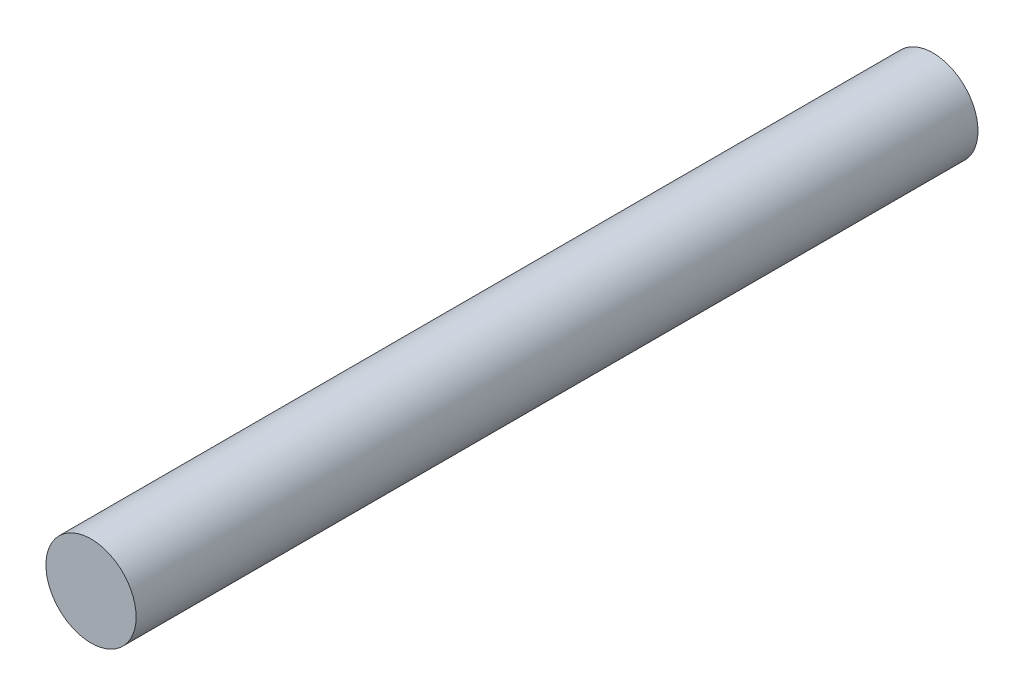
SolidWorks part; units mm, degrees
ref_plane "Front Plane" through (0, 0, 0) normal (0, 0, 1) x (1, 0, 0)
ref_plane "Top Plane" through (0, 0, 0) normal (0, 1, 0) x (1, 0, 0)
ref_plane "Right Plane" through (0, 0, 0) normal (1, 0, 0) x (0, 0, -1)
sketch "Sketch1" plane through (0, 0, 0) normal (0, 0, 1) x (1, 0, 0)
  circle A0 centre (0, 0) radius 1.5
  dimension "D1" = 3
extrude "Boss-Extrude1" add sketch "Sketch1" along normal blind 28
